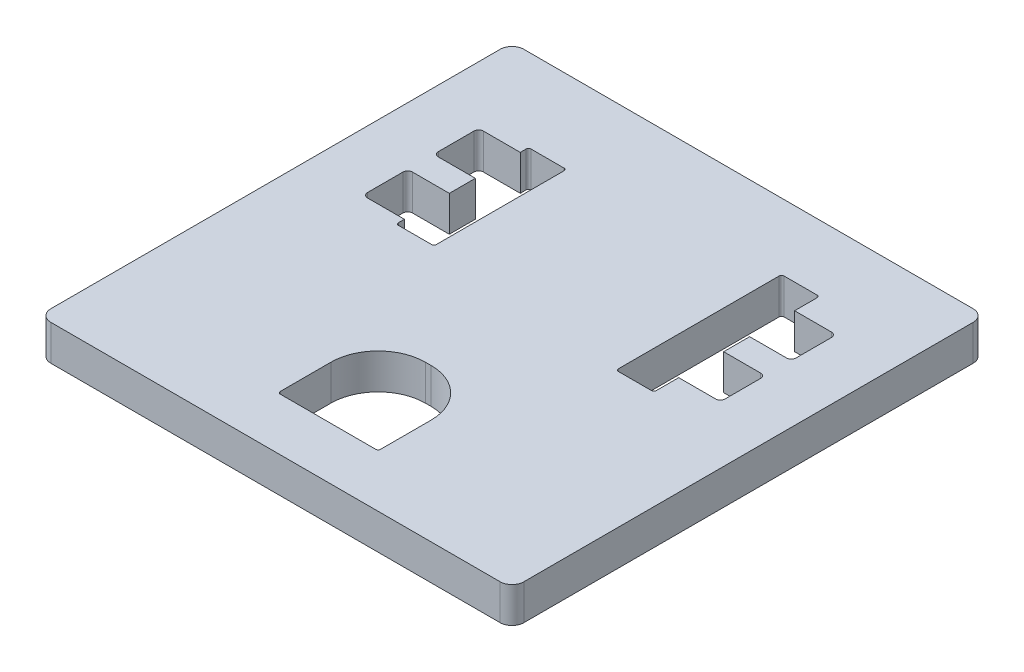
SolidWorks part; units mm, degrees
ref_plane "Front Plane" through (0, 0, 0) normal (0, 0, 1) x (1, 0, 0)
ref_plane "Top Plane" through (0, 0, 0) normal (0, 1, 0) x (1, 0, 0)
ref_plane "Right Plane" through (0, 0, 0) normal (1, 0, 0) x (0, 0, -1)
sketch "Sketch1" plane through (0, 0, 0) normal (0, 1, 0) x (1, 0, 0)
  line L1 (0.635, 0) -> (24.765, 0)
  line L2 (0, 0.635) -> (0, 24.765)
  line L3 (0.635, 25.4) -> (24.765, 25.4)
  line L4 (25.4, 0.635) -> (25.4, 24.765)
  arc A0 (24.765, 25.4) -> (25.4, 24.765) centre (24.765, 24.765) cw
  arc A1 (24.765, 0) -> (25.4, 0.635) centre (24.765, 0.635) ccw
  arc A2 (0.635, 0) -> (0, 0.635) centre (0.635, 0.635) cw
  arc A3 (0, 24.765) -> (0.635, 25.4) centre (0.635, 24.765) cw
  point P7 (25.4, 25.4)
  point P10 (25.4, 0)
  point P13 (0, 0)
  point P16 (0, 25.4)
  dimension "D3" = 0.635
  dimension "D1" = 25.4
  dimension "D2" = 25.4
extrude "Boss-Extrude1" add sketch "Sketch1" along normal blind 1.905
sketch "Sketch2" plane through (0, 1.905, 0) normal (0, 1, 0) x (1, 0, 0)
  line L0 (0, 24.765) -> (0, 0.635) construction
  line L1 (10.1346, 2.8194) -> (15.2654, 2.8194)
  line L2 (10.0076, 2.9464) -> (10.0076, 5.6642)
  line L3 (12.5476, 8.2042) -> (12.8524, 8.2042)
  line L4 (15.3924, 2.9464) -> (15.3924, 5.6642)
  line L5 (0.635, 0) -> (24.765, 0) construction
  line L6 (24.765, 25.4) -> (0.635, 25.4) construction
  line L7 (5.461, 20.955) -> (7.239, 20.955)
  line L8 (5.334, 20.828) -> (5.334, 20.5105)
  line L9 (5.461, 13.843) -> (7.239, 13.843)
  line L10 (7.366, 20.828) -> (7.366, 13.97)
  line L11 (18.161, 21.844) -> (19.939, 21.844)
  line L12 (18.034, 21.717) -> (18.034, 13.081)
  line L13 (18.161, 12.954) -> (19.939, 12.954)
  line L14 (20.066, 21.717) -> (20.066, 20.5105)
  line L15 (3.3528, 20.5105) -> (5.334, 20.5105)
  line L16 (3.0988, 20.2565) -> (3.0988, 18.3515)
  line L17 (3.3528, 18.0975) -> (5.334, 18.0975)
  line L18 (5.334, 14.2875) -> (5.334, 13.97)
  line L19 (3.3528, 16.7005) -> (5.334, 16.7005)
  line L20 (3.0988, 16.4465) -> (3.0988, 14.5415)
  line L21 (3.3528, 14.2875) -> (5.334, 14.2875)
  line L22 (20.066, 14.2875) -> (20.066, 13.081)
  line L23 (22.0472, 20.5105) -> (20.066, 20.5105)
  line L24 (22.3012, 20.2565) -> (22.3012, 18.3515)
  line L25 (22.0472, 18.0975) -> (20.066, 18.0975)
  line L27 (22.0472, 16.7005) -> (20.066, 16.7005)
  line L28 (22.3012, 16.4465) -> (22.3012, 14.5415)
  line L29 (22.0472, 14.2875) -> (20.066, 14.2875)
  line L30 (20.066, 18.0975) -> (20.066, 16.7005)
  line L31 (5.334, 18.0975) -> (5.334, 16.7005)
  arc A0 (15.2654, 2.8194) -> (15.3924, 2.9464) centre (15.2654, 2.9464) ccw
  arc A1 (10.1346, 2.8194) -> (10.0076, 2.9464) centre (10.1346, 2.9464) cw
  arc A2 (12.8524, 8.2042) -> (15.3924, 5.6642) centre (12.8524, 5.6642) cw
  arc A3 (10.0076, 5.6642) -> (12.5476, 8.2042) centre (12.5476, 5.6642) cw
  arc A4 (18.034, 13.081) -> (18.161, 12.954) centre (18.161, 13.081) ccw
  arc A5 (19.939, 12.954) -> (20.066, 13.081) centre (19.939, 13.081) ccw
  arc A6 (19.939, 21.844) -> (20.066, 21.717) centre (19.939, 21.717) cw
  arc A7 (18.161, 21.844) -> (18.034, 21.717) centre (18.161, 21.717) ccw
  arc A8 (7.239, 20.955) -> (7.366, 20.828) centre (7.239, 20.828) cw
  arc A9 (5.461, 20.955) -> (5.334, 20.828) centre (5.461, 20.828) ccw
  arc A10 (5.334, 13.97) -> (5.461, 13.843) centre (5.461, 13.97) ccw
  arc A11 (7.239, 13.843) -> (7.366, 13.97) centre (7.239, 13.97) ccw
  arc A12 (22.3012, 14.5415) -> (22.0472, 14.2875) centre (22.0472, 14.5415) cw
  arc A13 (22.0472, 16.7005) -> (22.3012, 16.4465) centre (22.0472, 16.4465) cw
  arc A14 (22.3012, 18.3515) -> (22.0472, 18.0975) centre (22.0472, 18.3515) cw
  arc A15 (22.0472, 20.5105) -> (22.3012, 20.2565) centre (22.0472, 20.2565) cw
  arc A16 (3.3528, 20.5105) -> (3.0988, 20.2565) centre (3.3528, 20.2565) ccw
  arc A17 (3.0988, 18.3515) -> (3.3528, 18.0975) centre (3.3528, 18.3515) ccw
  arc A18 (3.3528, 16.7005) -> (3.0988, 16.4465) centre (3.3528, 16.4465) ccw
  arc A19 (3.0988, 14.5415) -> (3.3528, 14.2875) centre (3.3528, 14.5415) ccw
  point P42 (12.7, 25.4)
  dimension "D5" = 0.127
  dimension "D6" = 2.54
  dimension "D27" = 0.127
  dimension "D28" = 0.254
  dimension "D1" = 10.0076
  dimension "D2" = 15.3924
  dimension "D3" = 2.8194
  dimension "D4" = 8.2042
  dimension "D7" = 13.843
  dimension "D8" = 20.955
  dimension "D9" = 12.954
  dimension "D10" = 21.844
  dimension "D11" = 5.334
  dimension "D12" = 5.334
  dimension "D13" = 7.366
  dimension "D14" = 7.366
  dimension "D15" = 9.6012
  dimension "D16" = 9.6012
  dimension "D17" = 9.6012
  dimension "D18" = 9.6012
  dimension "D19" = 14.2875
  dimension "D20" = 14.2875
  dimension "D21" = 16.7005
  dimension "D22" = 16.7005
  dimension "D23" = 18.0975
  dimension "D24" = 18.0975
  dimension "D25" = 20.5105
  dimension "D26" = 20.5105
extrude "Cut-Extrude1" cut sketch "Sketch2" against normal through all
